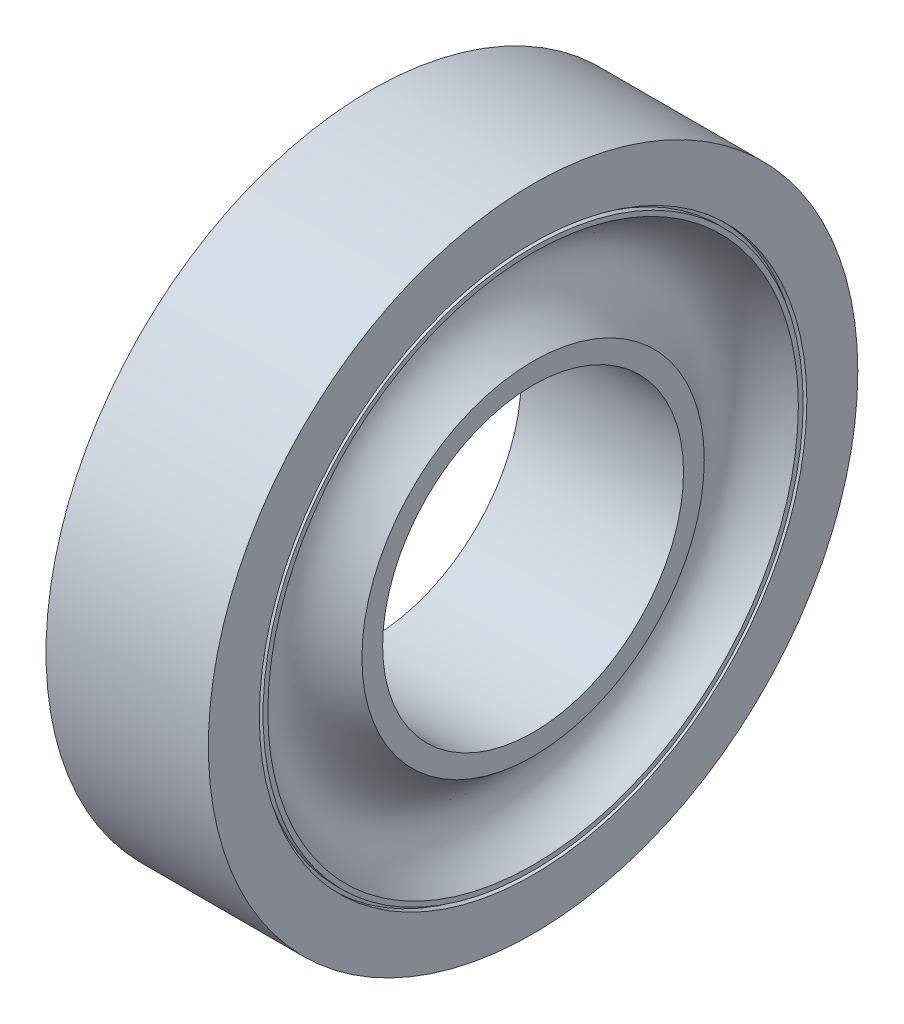
SolidWorks part; units mm, degrees
ref_plane "Front Plane" through (0, 0, 0) normal (0, 0, 1) x (1, 0, 0)
ref_plane "Top Plane" through (0, 0, 0) normal (0, 1, 0) x (1, 0, 0)
ref_plane "Right Plane" through (0, 0, 0) normal (1, 0, 0) x (0, 0, -1)
sketch "Sketch1" plane through (0, 0, 0) normal (0, 0, 1) x (1, 0, 0)
  line L0 (37.4228, 0) -> (-48.477, 0) construction
  line L1 (0, 55.955) -> (0, -45.0267) construction
  line L2 (7.5, 13.9) -> (-7.5, 13.9)
  line L3 (-7.5, 13.9) -> (-7.5, 15.815)
  line L4 (-7.5, 24.5077) -> (-7.5, 24.9503)
  line L5 (-7.5, 24.9503) -> (-6.9581, 24.9503)
  line L6 (-6.9581, 24.9503) -> (-6.9581, 25.2929)
  line L7 (-6.9581, 25.2929) -> (-7.5, 25.2929)
  line L8 (-7.5, 25.2929) -> (-7.5, 30)
  line L9 (-7.5, 30) -> (7.5, 30)
  line L10 (7.5, 25.2929) -> (7.5, 30)
  line L11 (6.9581, 25.2929) -> (7.5, 25.2929)
  line L12 (6.9581, 24.9503) -> (6.9581, 25.2929)
  line L13 (7.5, 24.9503) -> (6.9581, 24.9503)
  line L14 (7.5, 24.5077) -> (7.5, 24.9503)
  line L15 (7.5, 13.9) -> (7.5, 15.815)
  spline S0 degree 2 poles (-7.5, 15.815) (-0.2215, 20.8548) (-7.5, 24.5077) knots 0 0 0 1 1 1
  spline S1 degree 2 poles (7.5, 15.815) (0.2215, 20.8548) (7.5, 24.5077) knots 0 0 0 1 1 1
  point P5 (-7.5, 27.6465)
  point P25 (0, 30)
  point P30 (0, 13.9)
  dimension "D1" = 27.8
  dimension "D2" = 60
  dimension "D3" = 15
revolve "Revolve1" add sketch "Sketch1" angle 360 about L0
